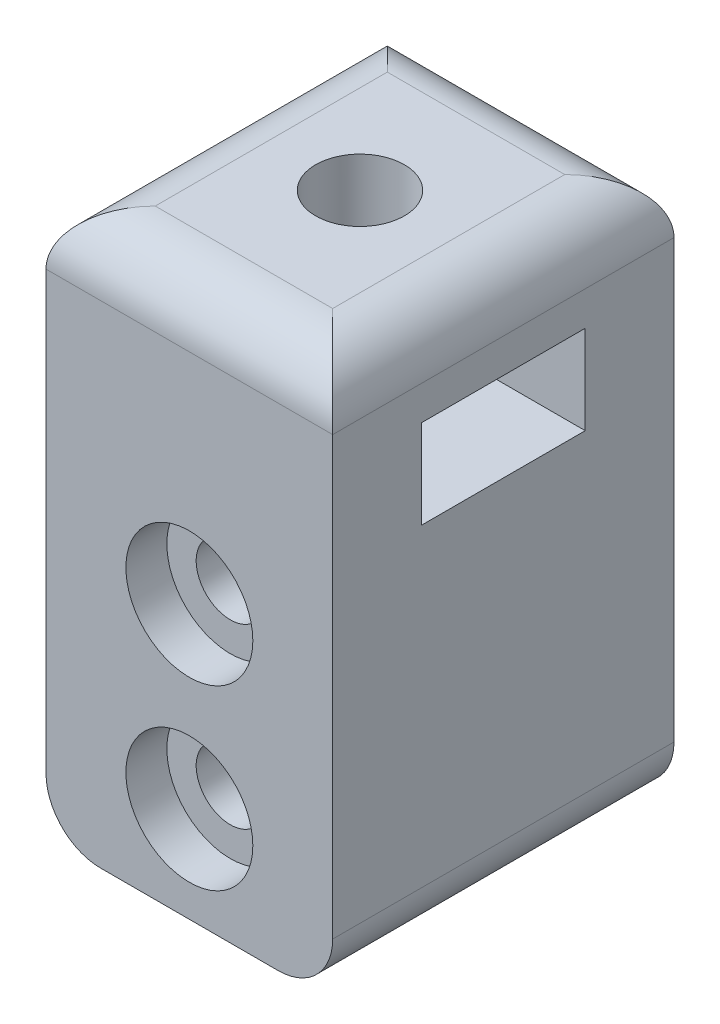
SolidWorks part; units mm, degrees
ref_plane "Alzado" through (0, 0, 0) normal (0, 0, 1) x (1, 0, 0)
ref_plane "Planta" through (0, 0, 0) normal (0, 1, 0) x (1, 0, 0)
ref_plane "Vista lateral" through (0, 0, 0) normal (1, 0, 0) x (0, 0, -1)
sketch "Croquis1" plane through (0, 0, 0) normal (0, 1, 0) x (1, 0, 0)
  line L0 (-8.75, 9.55) -> (12.25, 9.55)
  line L1 (12.25, -15.45) -> (-8.75, -15.45)
  line L5 (-8.75, 9.55) -> (-8.75, -15.45)
  line L7 (12.25, 9.55) -> (12.25, -15.45)
  dimension "D2" = 25
  dimension "D3" = 21
extrude "Saliente-Extruir1" add sketch "Croquis1" along normal blind 20
sketch "Croquis2" plane through (0, 20, 0) normal (0, 1, 0) x (1, 0, 0)
  line L16 (-8.75, 9.55) -> (-8.75, -15.45)
  line L19 (12.25, 9.55) -> (12.25, -15.45)
  line L22 (-8.75, -15.45) -> (12.25, -15.45)
  line L23 (12.25, 9.55) -> (-8.75, 9.55)
  line L24 (12.25, -15.45) -> (12.25, 9.55) construction
  line L25 (-8.75, 9.55) -> (-8.75, -15.45) construction
  point P16 (-6, 0)
extrude "Saliente-Extruir2" add sketch "Croquis2" along normal blind 20
sketch "Croquis3" plane through (-8.75, 0, 0) normal (-1, 0, 0) x (0, 0, 1)
  line L0 (-3.05, 33.5) -> (-3.05, 27)
  line L2 (-3.05, 27) -> (8.95, 27)
  line L3 (8.95, 27) -> (8.95, 33.5)
  line L4 (2.95, 0) -> (2.95, 27) construction
  line L5 (-9.55, 0) -> (15.45, 0) construction
  line L6 (-3.05, 33.5) -> (8.95, 33.5)
  point P11 (2.95, 27)
  dimension "D1" = 12
  dimension "D2" = 6.5
  dimension "D3" = 27
extrude "Cortar-Extruir1" cut sketch "Croquis3" against normal up to next
sketch "Croquis5" plane through (0, 0, 0) normal (0, -1, 0) x (1, 0, 0)
  line L0 (1.75, 15.45) -> (1.75, 8.45) construction
  line L1 (-8.75, 15.45) -> (12.25, 15.45) construction
  line L2 (1.75, -9.55) -> (1.75, 0.45) construction
  line L3 (12.25, -9.55) -> (-8.75, -9.55) construction
  line L4 (-3, 8.45) -> (6.5, 8.45)
  line L5 (-3, 8.45) -> (-3, 4.95)
  line L6 (-3, 4.95) -> (6.5, 4.95)
  line L7 (6.5, 8.45) -> (6.5, 4.95)
  circle A0 centre (1.75, 0.45) radius 3.5
  point P10 (1.75, 8.45)
  point P11 (1.75, 15.45)
  dimension "D5" = 7
  dimension "D1" = 7
  dimension "D2" = 9.5
  dimension "D3" = 10
  dimension "D4" = 3.5
extrude "Cortar-Extruir3" cut sketch "Croquis5" against normal blind 25
sketch "Croquis6" plane through (0, 0, 15.45) normal (0, 0, 1) x (1, 0, 0)
  line L0 (1.75, 0) -> (1.75, 7) construction
  line L2 (-8.75, 0) -> (12.25, 0) construction
  circle A0 centre (1.75, 7) radius 4.65
  circle A1 centre (1.75, 20) radius 4.65
  dimension "D1" = 9.3
  dimension "D2" = 9.3
  dimension "D3" = 13
  dimension "D4" = 7
extrude "Cortar-Extruir4" cut sketch "Croquis6" against normal blind 3
sketch "Croquis7" plane through (0, 0, 12.45) normal (0, 0, 1) x (1, 0, 0)
  circle A0 centre (1.75, 20) radius 2.5
  circle A1 centre (1.75, 7) radius 2.5
  dimension "D1" = 5
  dimension "D2" = 5
extrude "Cortar-Extruir5" cut sketch "Croquis7" against normal up to surface (9.5505 mm away)
fillet "Redondeo4" radius 4 2 edges at (-8.75, 0, 2.95) (12.25, 0, 2.95)
sketch "Croquis8" plane through (0, 33.5, 0) normal (0, -1, 0) x (1, 0, 0)
  line L0 (1.75, 8.95) -> (1.75, -3.05) construction
  line L1 (12.25, 8.95) -> (-8.75, 8.95) construction
  line L2 (12.25, -3.05) -> (-8.75, -3.05) construction
  circle A0 centre (1.75, 2.95) radius 3.25
  dimension "D1" = 6.5
extrude "Cortar-Extruir6" cut sketch "Croquis8" against normal mid plane 19
fillet "Redondeo5" radius 4 4 edges at (1.75, 40, -9.55) (1.75, 40, 15.45) (-8.75, 40, 2.95) (12.25, 40, 2.95)
